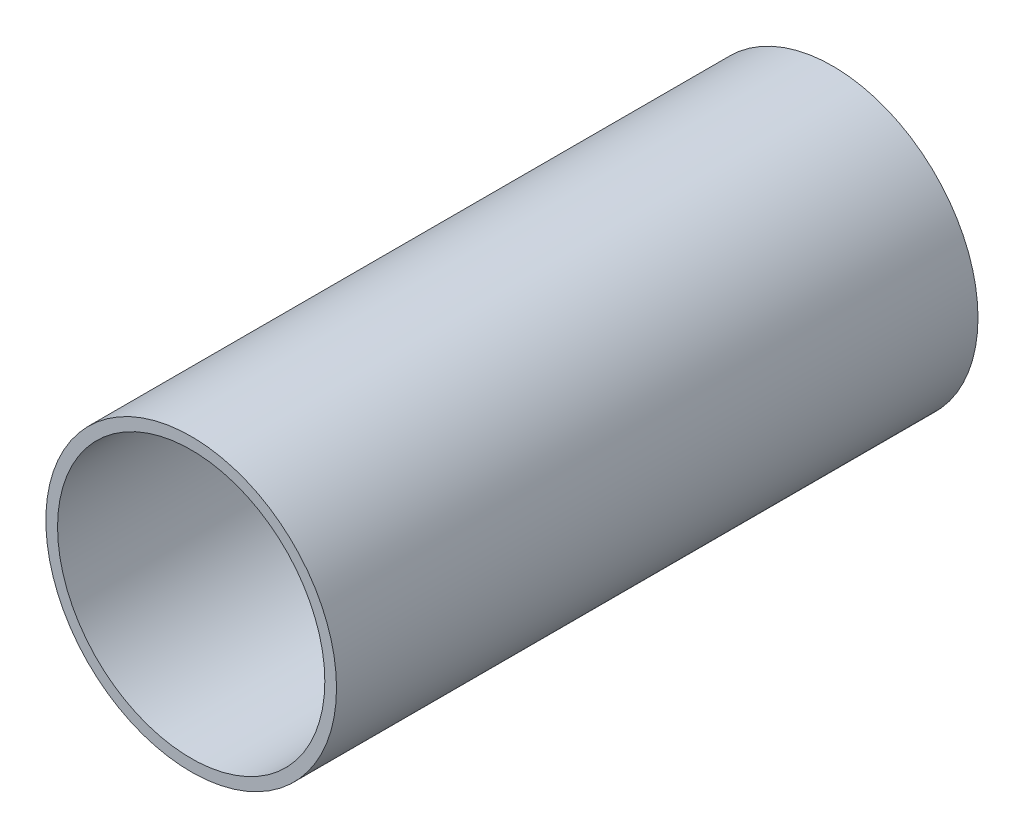
SolidWorks part; units mm, degrees
ref_plane "Alzado" through (0, 0, 0) normal (0, 0, 1) x (1, 0, 0)
ref_plane "Planta" through (0, 0, 0) normal (0, 1, 0) x (1, 0, 0)
ref_plane "Vista lateral" through (0, 0, 0) normal (1, 0, 0) x (0, 0, -1)
sketch "Croquis1" plane through (0, 0, 0) normal (0, 0, 1) x (1, 0, 0)
  circle A0 centre (0, 0) radius 40
  circle A1 centre (0, 0) radius 43.5
  dimension "D1" = 80
  dimension "D2" = 87
extrude "Saliente-Extruir1" add sketch "Croquis1" along normal blind 192
